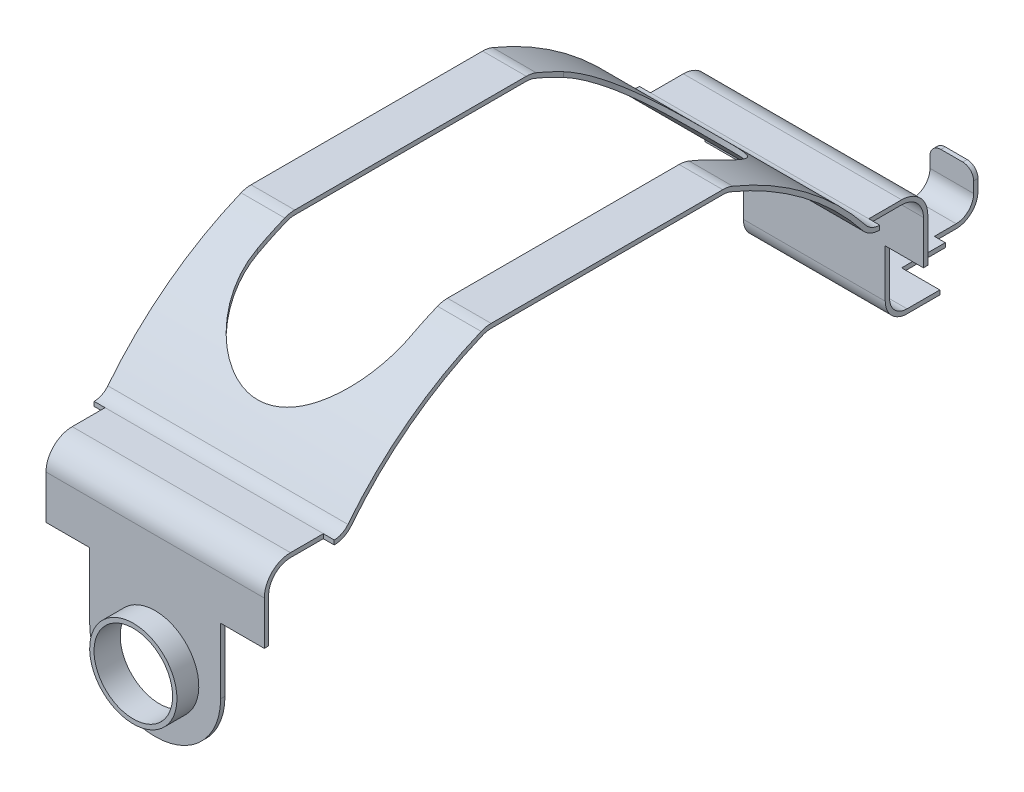
SolidWorks part; units mm, degrees
ref_plane "Front" through (0, 0, 0) normal (0, 0, 1) x (1, 0, 0)
ref_plane "Top" through (0, 0, 0) normal (0, 1, 0) x (1, 0, 0)
ref_plane "Right" through (0, 0, 0) normal (1, 0, 0) x (0, 0, -1)
sketch "Sketch3" plane through (0, 0, 0) normal (1, 0, 0) x (0, 0, -1)
  line L0 (-7.5, 5.5) -> (-7.5, 10)
  line L1 (-7.5, 10) -> (-6, 10)
  line L3 (-2.75, 12.5) -> (2.75, 12.5)
  line L5 (6, 10) -> (7.5, 10)
  line L6 (7.5, 10) -> (7.5, 6.9)
  line L7 (7.5, 6.9) -> (10.75, 6.9)
  line L8 (10.75, 6.9) -> (10.75, 7.9)
  arc A2 (-2.75, 12.5) -> (-6, 10) centre (0, 5.5625) ccw
  arc A3 (2.75, 12.5) -> (6, 10) centre (0, 5.5625) cw
  dimension "D1" = 15
  dimension "D4" = 5.5
  dimension "D8" = 1
  dimension "D10" = 12
sketch "Sketch4" plane through (0, 0, 0) normal (1, 0, 0) x (0, 0, -1)
  line L0 (-2.6528, 12.6) -> (2.6528, 12.6)
  line L1 (-7.5, 10) -> (-6, 10) construction
  line L2 (6, 10) -> (7.5, 10) construction
  line L3 (-2.75, 12.5) -> (2.75, 12.5) construction
  line L4 (6.247, 10) -> (6.247, 10.1)
  line L5 (-6.247, 10.1) -> (-6.247, 10)
  line L6 (-7.5, 10) -> (-6.247, 10) construction
  line L7 (6.247, 10) -> (7.5, 10) construction
  line L8 (-2.6528, 12.5) -> (2.6528, 12.5)
  arc A0 (2.8433, 12.4623) -> (2.6528, 12.5) centre (2.6528, 12) ccw
  arc A1 (6, 10) -> (2.75, 12.5) centre (0, 5.5625) ccw construction
  arc A2 (-2.75, 12.5) -> (-6, 10) centre (0, 5.5625) ccw construction
  arc A3 (5.8547, 10.19) -> (2.8433, 12.4623) centre (0, 5.5625) ccw
  arc A4 (-2.8433, 12.4623) -> (-5.8547, 10.19) centre (0, 5.5625) ccw
  arc A5 (6.247, 10) -> (5.8547, 10.19) centre (6.247, 10.5) cw
  arc A6 (-2.6528, 12.5) -> (-2.8433, 12.4623) centre (-2.6528, 12) ccw
  arc A7 (-6.247, 10) -> (-5.8547, 10.19) centre (-6.247, 10.5) ccw
  arc A8 (-6.247, 10.1) -> (-5.9332, 10.252) centre (-6.247, 10.5) ccw
  arc A9 (-2.8814, 12.5547) -> (-5.9332, 10.252) centre (0, 5.5625) ccw
  arc A10 (-2.6528, 12.6) -> (-2.8814, 12.5547) centre (-2.6528, 12) ccw
  arc A11 (2.8814, 12.5547) -> (2.6528, 12.6) centre (2.6528, 12) ccw
  arc A12 (5.9332, 10.252) -> (2.8814, 12.5547) centre (0, 5.5625) ccw
  arc A13 (6.247, 10.1) -> (5.9332, 10.252) centre (6.247, 10.5) cw
  dimension "D1" = 0.5
  dimension "D2" = 0.1
extrude "Extrude1" add sketch "Sketch4" along normal mid plane 5.5
sketch "Sketch5" plane through (0, 0, 0) normal (0, 1, 0) x (1, 0, 0)
  line L0 (0, -992.5376) -> (0, 49007.4624) construction
  line L1 (0, -3.905) -> (0, 3.905) construction
  line L2 (1.75, -3.5) -> (1.75, 3.5)
  line L3 (-3.025, 0) -> (3.025, 0) construction
  line L4 (-1.75, -3.5) -> (-1.75, 3.5)
  arc A0 (1.75, 3.5) -> (-1.75, 3.5) centre (0, 3.5) ccw
  arc A1 (1.75, -3.5) -> (-1.75, -3.5) centre (0, -3.5) cw
  point P6 (1.75, 0)
  dimension "D1" = 10.5
  dimension "D2" = 3.5
extrude "Cut-Extrude1" cut sketch "Sketch5" along normal through all
sketch "Sketch6" plane through (0, 0, 0) normal (1, 0, 0) x (0, 0, -1)
  line L0 (6.247, 10) -> (7, 10)
  line L1 (7.5, 10) -> (7.5, 6.9) construction
  line L2 (7.5, 9.5) -> (7.5, 8.5)
  line L3 (6.247, 10.1) -> (7, 10.1)
  line L4 (6.247, 10.1) -> (6.247, 10)
  line L5 (7.6, 9.5) -> (7.6, 8.5)
  line L6 (6, 10) -> (7.5, 10) construction
  line L7 (7.5, 8.5) -> (7.6, 8.5)
  line L8 (0, -991.2289) -> (0, 49008.7711) construction
  line L9 (0, 55) -> (0, -55) construction
  line L10 (-7.5, 8.5) -> (-7.6, 8.5)
  line L11 (-7.6, 9.5) -> (-7.6, 8.5)
  line L12 (-6.247, 10.1) -> (-6.247, 10)
  line L13 (-6.247, 10.1) -> (-7, 10.1)
  line L14 (-7.5, 9.5) -> (-7.5, 8.5)
  line L15 (-6.247, 10) -> (-7, 10)
  arc A0 (7, 10) -> (7.5, 9.5) centre (7, 9.5) cw
  arc A1 (7, 10.1) -> (7.6, 9.5) centre (7, 9.5) cw
  arc A2 (-7, 10.1) -> (-7.6, 9.5) centre (-7, 9.5) ccw
  arc A3 (-7, 10) -> (-7.5, 9.5) centre (-7, 9.5) ccw
  dimension "D1" = 0.5
  dimension "D3" = 1.5
  dimension "D2" = 0.1
extrude "Extrude2" add sketch "Sketch6" along normal mid plane 5
sketch "Sketch7" plane through (0, 0, 0) normal (1, 0, 0) x (0, 0, -1)
  line L0 (7.5, 10) -> (7.5, 6.9) construction
  line L1 (7.5, 6.9) -> (10.75, 6.9) construction
  line L2 (7.5, 8.5) -> (7.5, 7.4)
  line L3 (8, 6.9) -> (8.75, 6.9)
  line L4 (7.6, 8.5) -> (7.6, 7.4)
  line L5 (8, 7) -> (8.75, 7)
  line L6 (8.75, 6.9) -> (8.75, 7)
  line L7 (7.6, 8.5) -> (7.5, 8.5)
  arc A0 (7.5, 7.4) -> (8, 6.9) centre (8, 7.4) ccw
  arc A1 (7.6, 7.4) -> (8, 7) centre (8, 7.4) ccw
  dimension "D2" = 0.5
  dimension "D1" = 1.25
  dimension "D3" = 0.1
extrude "Extrude3" add sketch "Sketch7" along normal mid plane 3.25
sketch "Sketch8" plane through (0, 0, 0) normal (1, 0, 0) x (0, 0, -1)
  line L0 (8.75, 7) -> (9.75, 7)
  line L1 (9.75, 7) -> (9.75, 6.9)
  line L2 (7.5, 6.9) -> (10.75, 6.9) construction
  line L3 (9.75, 6.9) -> (8.75, 6.9)
  line L4 (8.75, 6.9) -> (8.75, 7) construction
  line L5 (8.75, 6.9) -> (8.75, 7)
  dimension "D1" = 1
extrude "Extrude4" add sketch "Sketch8" along normal mid plane 1.5
sketch "Sketch9" plane through (0, 0, 0) normal (1, 0, 0) x (0, 0, -1)
  line L0 (10.75, 6.9) -> (10.75, 7.9) construction
  line L1 (7.5, 6.9) -> (10.75, 6.9) construction
  line L2 (10.75, 7.4) -> (10.75, 7.9)
  line L3 (9.75, 6.9) -> (10.25, 6.9)
  line L4 (9.75, 7) -> (10.25, 7)
  line L5 (10.65, 7.4) -> (10.65, 7.9)
  line L6 (10.65, 7.9) -> (10.75, 7.9)
  line L7 (9.75, 6.9) -> (9.75, 7)
  arc A0 (10.75, 7.4) -> (10.25, 6.9) centre (10.25, 7.4) cw
  arc A1 (10.65, 7.4) -> (10.25, 7) centre (10.25, 7.4) cw
  dimension "D1" = 0.5
  dimension "D2" = 0.1
extrude "Extrude5" add sketch "Sketch9" along normal mid plane 1
ref_plane "Plane1" through (0, 0, 7.5) normal (0, 0, 1) x (1, 0, 0)
sketch "Sketch10" plane through (0, 0, 7.5) normal (0, 0, 1) x (1, 0, 0)
  line L0 (-1.5, 8.5) -> (-1.5, 7)
  line L1 (2.5, 8.5) -> (-2.5, 8.5) construction
  line L2 (0, -55) -> (0, 55) construction
  line L3 (0, -992.5126) -> (0, 49007.4874) construction
  line L4 (1.5, 8.5) -> (1.5, 7)
  line L5 (1.5, 8.5) -> (-1.5, 8.5)
  arc A0 (-1.5, 7) -> (1.5, 7) centre (0, 7) ccw
  dimension "D1" = 1.5
extrude "Extrude6" add sketch "Sketch10" along normal blind 0.1
sketch "Sketch11" plane through (0, 0, 7.6) normal (0, 0, 1) x (1, 0, 0)
  circle A0 centre (0, 7) radius 1
  circle A1 centre (0, 7) radius 0.9
  dimension "D1" = 2
  dimension "D2" = 0.1
extrude "Extrude7" add sketch "Sketch11" along normal blind 0.5
sketch "Sketch12" plane through (0, 0, 7.6) normal (0, 0, 1) x (1, 0, 0)
  circle A1 centre (0, 7) radius 0.9
  circle A2 centre (0, 7) radius 0.9
  dimension "D1" = 0
extrude "Cut-Extrude2" cut sketch "Sketch12" against normal up to next
fillet "Fillet1" radius 0.25 2 edges at (0.5, 7.9, -10.7) (-0.5, 7.9, -10.7)
